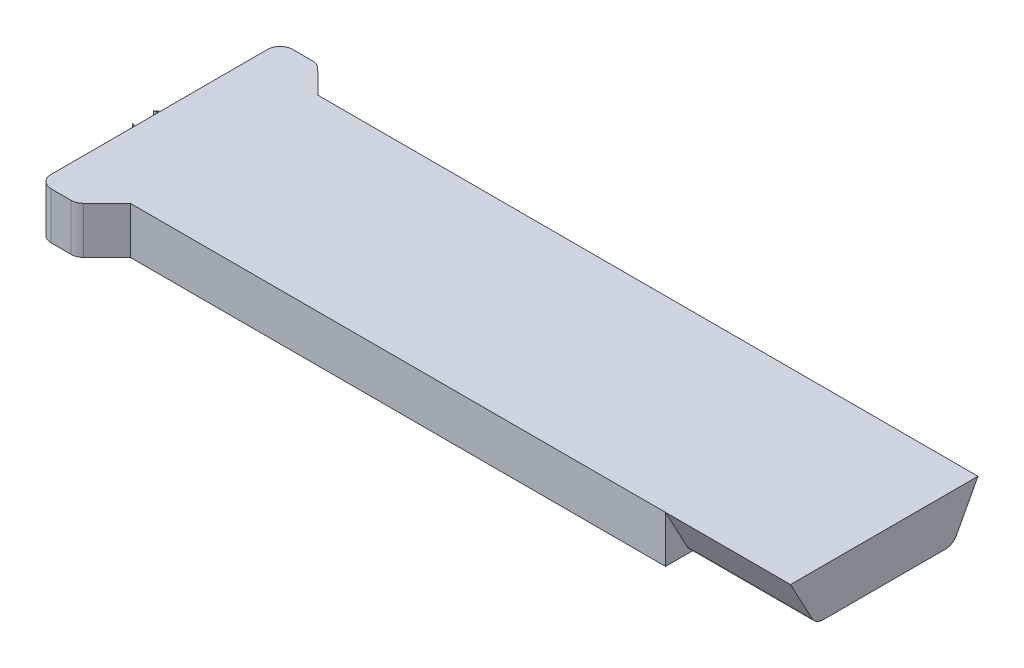
SolidWorks part; units mm, degrees
ref_plane "Front Plane" through (0, 0, 0) normal (0, 0, 1) x (1, 0, 0)
ref_plane "Top Plane" through (0, 0, 0) normal (0, 1, 0) x (1, 0, 0)
ref_plane "Right Plane" through (0, 0, 0) normal (1, 0, 0) x (0, 0, -1)
sketch "Sketch1" plane through (0, 0, 0) normal (0, 1, 0) x (1, 0, 0)
  line L0 (-1397, 0) -> (1397, 0) construction
  line L1 (-1284.8768, -381) -> (1397, -381)
  line L2 (-1284.8768, 381) -> (1397, 381)
  line L3 (1397, 381) -> (1397, -381)
  line L4 (-1397, -490.7407) -> (-1397, 490.7407)
  line L5 (-1397, 490.7407) -> (-1284.8768, 381)
  line L6 (-1397, -490.7407) -> (-1284.8768, -381)
  point P4 (0, 0)
  dimension "D1" = 2794
extrude "Boss-Extrude1" add sketch "Sketch1" along normal blind 190.5
sketch "Sketch3" plane through (-1397, 0, 0) normal (-1, 0, 0) x (0, 0, 1)
  line L4 (-490.7407, 0) -> (490.7407, 0)
  line L5 (490.7407, 0) -> (490.7407, 190.5)
  line L6 (490.7407, 190.5) -> (-490.7407, 190.5)
  line L7 (-490.7407, 190.5) -> (-490.7407, 0)
  line L8 (-490.7407, 0) -> (490.7407, 0)
  line L9 (490.7407, 0) -> (490.7407, 190.5)
  line L10 (490.7407, 190.5) -> (-490.7407, 190.5)
  line L11 (-490.7407, 190.5) -> (-490.7407, 0)
  dimension "D1" = 0
extrude "Boss-Extrude2" add sketch "Sketch3" along normal blind 152.4
fillet "Fillet2" radius 50.8 4 edges at (-1397, 95.25, 490.7407) (-1397, 95.25, -490.7407) (-1549.4, 95.25, -490.7407) (-1549.4, 95.25, 490.7407)
sketch "Sketch4" plane through (1397, 0, 0) normal (1, 0, 0) x (0, 0, -1)
  line L0 (-381, 190.5) -> (-279.4, 0)
  line L1 (381, 190.5) -> (279.4, 0)
  line L2 (279.4, 0) -> (381, 0)
  line L4 (-381, 0) -> (381, 0)
  line L5 (381, 0) -> (381, 190.5)
  line L6 (381, 190.5) -> (-381, 190.5)
  line L7 (-381, 190.5) -> (-381, 0)
  line L8 (-381, 0) -> (-279.4, 0)
  line L9 (381, 0) -> (381, 190.5)
  line L11 (-381, 190.5) -> (-381, 0)
  dimension "D2" = 101.6
  dimension "D3" = 101.6
  dimension "D1" = 0
extrude "Cut-Extrude1" cut sketch "Sketch4" against normal blind 508
fillet "Fillet3" radius 50.8 2 edges at (1143, 0, 279.4) (1143, 0, -279.4)
sketch "Sketch6" plane through (0, 0, 0) normal (0, -1, 0) x (1, 0, 0)
  line L0 (-1549.4, 0) -> (-2187.5378, 0) construction
  line L1 (-1549.4, -439.9407) -> (-1549.4, 439.9407) construction
  line L2 (-1562.1, -50.8) -> (-1562.1, 50.8)
  line L3 (-1549.4, 63.5) -> (-1587.5, 63.5)
  line L4 (-1562.1, 50.8) -> (-1549.4, 50.8) construction
  line L5 (-1587.5, 63.5) -> (-1587.5, 50.8)
  line L6 (-1587.5, 50.8) -> (-1562.1, 50.8)
  line L7 (-1587.5, -50.8) -> (-1562.1, -50.8)
  line L8 (-1587.5, -63.5) -> (-1587.5, -50.8)
  line L9 (-1549.4, -63.5) -> (-1587.5, -63.5)
  line L12 (1397, -248.92) -> (1397, 248.92)
  line L13 (1397, 248.92) -> (889, 248.92)
  line L14 (889, 248.92) -> (889, 381)
  line L15 (889, 381) -> (-1284.8768, 381)
  line L16 (-1284.8768, 381) -> (-1382.19, 476.2453)
  line L17 (-1417.7232, 490.7407) -> (-1498.6, 490.7407)
  line L18 (-1549.4, 439.9407) -> (-1549.4, -439.9407)
  line L19 (-1498.6, -490.7407) -> (-1417.7232, -490.7407)
  line L20 (-1382.19, -476.2453) -> (-1284.8768, -381)
  line L21 (-1284.8768, -381) -> (889, -381)
  line L22 (889, -381) -> (889, -248.92)
  line L23 (889, -248.92) -> (1397, -248.92)
  line L24 (1397, -248.92) -> (1397, 248.92)
  line L25 (1397, 248.92) -> (889, 248.92)
  line L26 (889, 248.92) -> (889, 381)
  line L27 (889, 381) -> (-1284.8768, 381)
  line L28 (-1284.8768, 381) -> (-1382.19, 476.2453)
  line L29 (-1417.7232, 490.7407) -> (-1498.6, 490.7407)
  line L30 (-1549.4, 63.5) -> (-1549.4, -63.5)
  line L31 (-1498.6, -490.7407) -> (-1417.7232, -490.7407)
  line L32 (-1382.19, -476.2453) -> (-1284.8768, -381)
  line L33 (-1284.8768, -381) -> (889, -381)
  line L34 (889, -381) -> (889, -248.92)
  line L35 (889, -248.92) -> (1397, -248.92)
  arc A4 (-1382.19, 476.2453) -> (-1417.7232, 490.7407) centre (-1417.7232, 439.9407) ccw
  arc A5 (-1498.6, 490.7407) -> (-1549.4, 439.9407) centre (-1498.6, 439.9407) ccw
  arc A6 (-1549.4, -439.9407) -> (-1498.6, -490.7407) centre (-1498.6, -439.9407) ccw
  arc A7 (-1417.7232, -490.7407) -> (-1382.19, -476.2453) centre (-1417.7232, -439.9407) ccw
  arc A8 (-1382.19, 476.2453) -> (-1417.7232, 490.7407) centre (-1417.7232, 439.9407) ccw
  arc A9 (-1498.6, 490.7407) -> (-1549.4, 439.9407) centre (-1498.6, 439.9407) ccw
  arc A10 (-1549.4, -439.9407) -> (-1498.6, -490.7407) centre (-1498.6, -439.9407) ccw
  arc A11 (-1417.7232, -490.7407) -> (-1382.19, -476.2453) centre (-1417.7232, -439.9407) ccw
  point P28 (-1562.1, 0)
  line M30 (-1549.4, 439.9407) -> (-1549.4, -439.9407)
  dimension "D2" = 12.7
  dimension "D3" = 50.8
  dimension "D4" = 12.7
  dimension "D5" = 38.1
  dimension "D1" = 0
extrude "Boss-Extrude3" add sketch "Sketch6" against normal blind 139.7 contours L9 L3 L5 L6 L2 L7 L8 M30
sketch "Sketch7" plane through (0, 139.7, 0) normal (0, 1, 0) x (1, 0, 0)
  line L0 (-1587.5, 63.5) -> (-1615.9366, 43.1804)
  line L1 (-1615.9366, 43.1804) -> (-1587.5, 50.8)
  line L2 (-1666.1091, 0) -> (-1458.0909, 0) construction
  line L3 (-1615.9366, -43.1804) -> (-1587.5, -50.8)
  line L4 (-1587.5, -63.5) -> (-1587.5, -50.8)
  line L5 (-1587.5, -63.5) -> (-1615.9366, -43.1804)
  line L8 (-1549.4, 63.5) -> (-1587.5, 63.5)
  line L9 (-1587.5, 63.5) -> (-1587.5, 50.8)
  line L10 (-1587.5, 50.8) -> (-1562.1, 50.8)
  line L11 (-1562.1, 50.8) -> (-1562.1, -50.8)
  line L12 (-1562.1, -50.8) -> (-1587.5, -50.8)
  line L13 (-1587.5, -50.8) -> (-1587.5, -63.5)
  line L14 (-1587.5, -63.5) -> (-1549.4, -63.5)
  line L15 (-1549.4, -63.5) -> (-1549.4, 63.5)
  line L17 (-1587.5, 63.5) -> (-1587.5, 50.8)
  point P10 (-1562.1, 0)
  dimension "D2" = 105
  dimension "D3" = 34.9503
  dimension "D1" = 0
extrude "Boss-Extrude4" add sketch "Sketch7" along normal blind 139.7 from surface at -139.7 starting at face at (-854.4491, 0, 0)
sketch "Sketch8" plane through (-1562.1, 0, 0) normal (-1, 0, 0) x (0, 0, 1)
  line L0 (0, 139.7) -> (0, 0) construction
  line L1 (-50.8, 139.7) -> (50.8, 139.7) construction
  circle A0 centre (0, 106.68) radius 15.24
  circle A1 centre (0, 33.02) radius 15.24
  dimension "D1" = 30.48
  dimension "D2" = 30.48
  dimension "D3" = 33.02
  dimension "D4" = 33.02
extrude "Cut-Extrude2" cut sketch "Sketch8" against normal blind 12.7
sketch "Sketch9" plane through (0, 0, -63.5) normal (0, 0, -1) x (-1, 0, 0)
  line L0 (1568.45, 139.7) -> (1568.45, 0) construction
  line L1 (1549.4, 139.7) -> (1587.5, 139.7) construction
  line L2 (1549.4, 0) -> (1587.5, 0) construction
  line L3 (1587.5, 139.7) -> (1587.5, 0) construction
  circle A0 centre (1568.45, 106.68) radius 8.89
  circle A1 centre (1568.45, 33.02) radius 8.89
  dimension "D1" = 17.78
  dimension "D2" = 17.78
  dimension "D3" = 33.02
  dimension "D4" = 33.02
sketch "Sketch10" plane through (-1562.1, 0, 0) normal (-1, 0, 0) x (0, 0, 1)
  line L4 (-50.8, 0) -> (50.8, 0)
  line L5 (50.8, 0) -> (50.8, 139.7)
  line L6 (50.8, 139.7) -> (-50.8, 139.7)
  line L7 (-50.8, 139.7) -> (-50.8, 0)
  line L8 (-50.8, 0) -> (50.8, 0)
  line L9 (50.8, 0) -> (50.8, 139.7)
  line L10 (50.8, 139.7) -> (-50.8, 139.7)
  line L11 (-50.8, 139.7) -> (-50.8, 0)
  dimension "D1" = 0
extrude "Cut-Extrude4" cut sketch "Sketch10" against normal blind 7.112
extrude "Cut-Extrude5" cut sketch "Sketch9" against normal blind 179.07
fillet "Fillet4" radius 25.4 2 edges at (-1587.5, 69.85, -63.5) (-1587.5, 69.85, 63.5)
sketch "Sketch11" plane through (0, 190.5, 0) normal (0, 1, 0) x (1, 0, 0)
  line L0 (-1284.8768, 381) -> (-1284.8768, -381) construction
  line L1 (-897.6063, 381) -> (-897.6063, -381) construction
  line L2 (889, 381) -> (-1284.8768, 381) construction
  line L3 (-1284.8768, -381) -> (889, -381) construction
  line L4 (-1217.8119, 381) -> (-1217.8119, -381) construction
  line L5 (-1063.7673, -381) -> (-1063.7673, 381) construction
  line L6 (-1217.8119, 0) -> (-897.6063, 0) construction
  line L7 (-1101.8673, -88.4607) -> (-1101.8673, 88.4607)
  line L8 (-1101.8673, -88.4607) -> (-1087.6936, -115.4308)
  line L9 (-1087.6936, -115.4308) -> (-1039.841, -115.4308)
  line L10 (-1101.8673, 88.4607) -> (-1087.6936, 115.4308)
  line L11 (-1087.6936, 115.4308) -> (-1039.841, 115.4308)
  line L12 (-1025.6673, 88.4607) -> (-1039.841, 115.4308)
  line L13 (-1025.6673, -88.4607) -> (-1025.6673, 88.4607)
  line L14 (-1025.6673, -88.4607) -> (-1039.841, -115.4308)
  point P16 (-1063.7673, 0)
  point P19 (-1101.8673, 0)
  point P22 (-1025.6673, 0)
  point P25 (-1063.7673, 115.4308)
  point P28 (-1063.7673, -115.4308)
  dimension "D1" = 38.1
sketch "Sketch12" plane through (0, 190.5, 0) normal (0, 1, 0) x (1, 0, 0)
  line L0 (-897.6063, 0) -> (1397, 0) construction
  line L1 (1397, -381) -> (1397, 381) construction
  line L2 (889, 381) -> (1397, 381) construction
  line L3 (1143, 381) -> (1143, -385.1758) construction
  line L4 (889, 381) -> (889, -381) construction
  point P11 (1143, 0)
sketch "Sketch13" plane through (0, 0, -381) normal (0, 0, -1) x (-1, 0, 0)
  line L0 (1062.9558, 190.5) -> (1062.9558, 393.7) construction
  line L1 (-889, 190.5) -> (1284.8768, 190.5) construction
  circle A0 centre (1062.9558, 292.1) radius 50.8782 construction
  dimension "D2" = 101.7564
  dimension "D1" = 203.2
